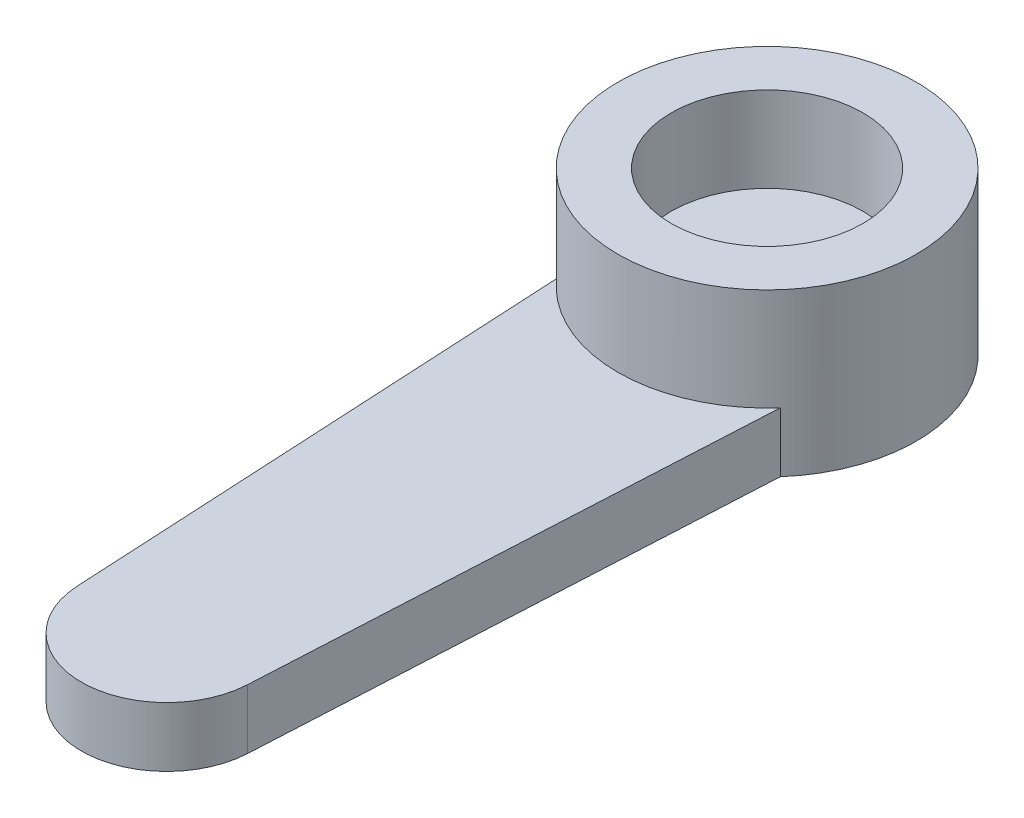
SolidWorks part; units mm, degrees
ref_plane "Front Plane" through (0, 0, 0) normal (0, 0, 1) x (1, 0, 0)
ref_plane "Top Plane" through (0, 0, 0) normal (0, 1, 0) x (1, 0, 0)
ref_plane "Right Plane" through (0, 0, 0) normal (1, 0, 0) x (0, 0, -1)
sketch "Sketch1" plane through (0, 0, 0) normal (0, 1, 0) x (1, 0, 0)
  circle A0 centre (0, 0) radius 3.5
  dimension "D1" = 7
extrude "Boss-Extrude1" add sketch "Sketch1" along normal blind 3.8
sketch "Sketch2" plane through (0, 0, 0) normal (0, -1, 0) x (1, 0, 0)
  line L0 (-2, 14.1925) -> (-2.625, 2.315)
  line L1 (2.625, 2.315) -> (2, 14.1925)
  circle A0 centre (0, 0) radius 3.5 construction
  arc A1 (-2, 14.1925) -> (2, 14.1925) centre (0, 14.0872) cw
  arc A2 (2.625, 2.315) -> (-2.625, 2.315) centre (0, 0) ccw
  point P7 (0, 0)
  point P8 (1.9734, 14.1136)
  dimension "D2" = 12.59
  dimension "D1" = 5.25
  dimension "D3" = 4
extrude "Boss-Extrude2" add sketch "Sketch2" against normal blind 1.4
sketch "Sketch3" plane through (0, 3.8, 0) normal (0, 1, 0) x (1, 0, 0)
  circle A0 centre (0, 0) radius 2.25
  dimension "D1" = 4.5
extrude "Cut-Extrude1" cut sketch "Sketch3" against normal blind 2
